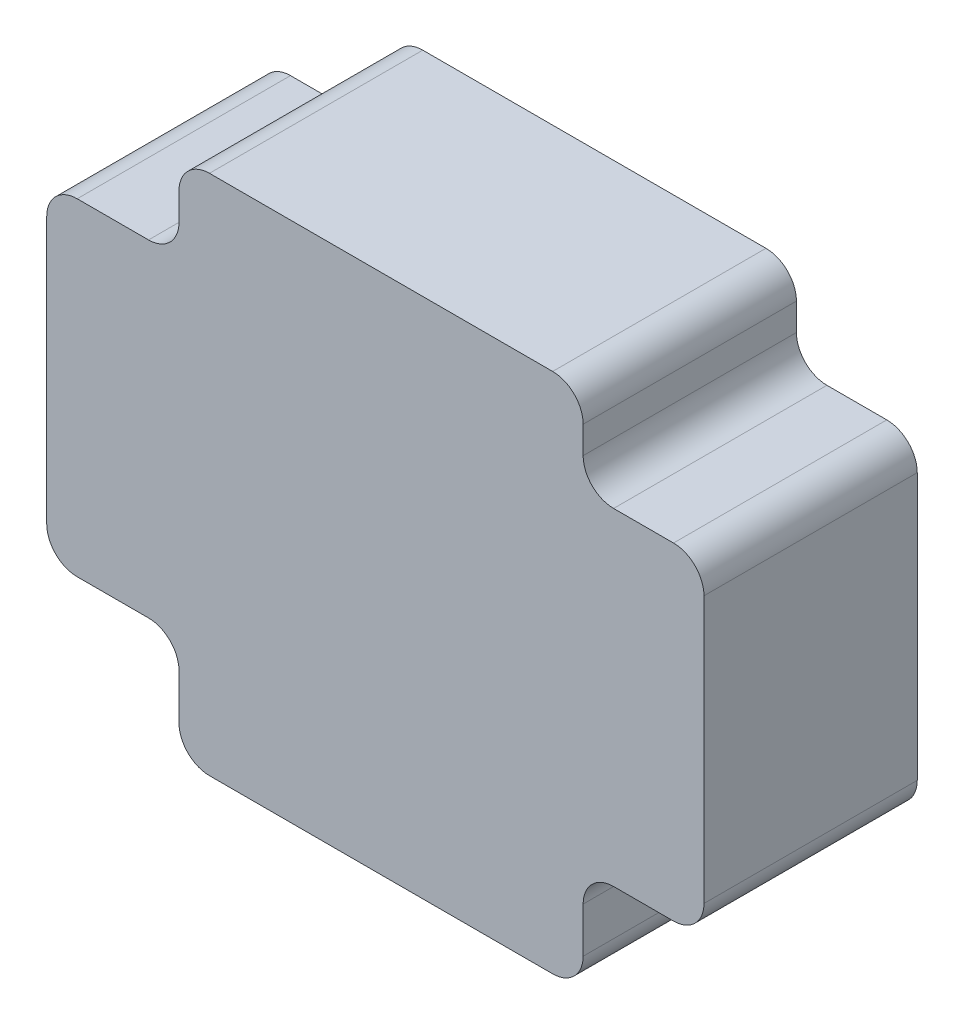
SolidWorks part; units mm, degrees
ref_plane "Front Plane" through (0, 0, 0) normal (0, 0, 1) x (1, 0, 0)
ref_plane "Top Plane" through (0, 0, 0) normal (0, 1, 0) x (1, 0, 0)
ref_plane "Right Plane" through (0, 0, 0) normal (1, 0, 0) x (0, 0, -1)
sketch "Sketch1" plane through (0, 0, 0) normal (0, 0, 1) x (1, 0, 0)
  line L0 (76.3168, 53.7233) -> (95.9729, 53.7233)
  line L1 (-99.7242, -53.7233) -> (-76.3168, -53.7233)
  line L2 (-109.7242, -43.7233) -> (-109.7242, 43.7233)
  line L3 (-99.7242, 53.7233) -> (-76.3168, 53.7233)
  line L4 (105.9729, -43.7233) -> (105.9729, 43.7233)
  line L7 (-56.3168, -88.5564) -> (56.3168, -88.5564)
  line L8 (-66.3168, -78.5564) -> (-66.3168, -63.7233)
  line L9 (-56.3168, 82.6615) -> (56.3168, 82.6615)
  line L10 (66.3168, -78.5564) -> (66.3168, -63.7233)
  line L15 (76.3168, -53.7233) -> (95.9729, -53.7233)
  line L16 (-66.3168, 63.7233) -> (-66.3168, 72.6615)
  line L17 (66.3168, 63.7233) -> (66.3168, 72.6615)
  arc A0 (-76.3168, -53.7233) -> (-66.3168, -63.7233) centre (-76.3168, -63.7233) cw
  arc A1 (66.3168, -63.7233) -> (76.3168, -53.7233) centre (76.3168, -63.7233) cw
  arc A2 (76.3168, 53.7233) -> (66.3168, 63.7233) centre (76.3168, 63.7233) cw
  arc A3 (-76.3168, 53.7233) -> (-66.3168, 63.7233) centre (-76.3168, 63.7233) ccw
  arc A4 (-109.7242, 43.7233) -> (-99.7242, 53.7233) centre (-99.7242, 43.7233) cw
  arc A5 (-99.7242, -53.7233) -> (-109.7242, -43.7233) centre (-99.7242, -43.7233) cw
  arc A6 (95.9729, -53.7233) -> (105.9729, -43.7233) centre (95.9729, -43.7233) ccw
  arc A7 (95.9729, 53.7233) -> (105.9729, 43.7233) centre (95.9729, 43.7233) cw
  arc A8 (56.3168, 82.6615) -> (66.3168, 72.6615) centre (56.3168, 72.6615) cw
  arc A9 (-66.3168, 72.6615) -> (-56.3168, 82.6615) centre (-56.3168, 72.6615) cw
  arc A10 (56.3168, -88.5564) -> (66.3168, -78.5564) centre (56.3168, -78.5564) ccw
  arc A11 (-56.3168, -88.5564) -> (-66.3168, -78.5564) centre (-56.3168, -78.5564) cw
  point P0 (0, 0)
  point P5 (0, 0)
  point P21 (66.3168, 53.7233)
  point P24 (-66.3168, 53.7233)
  point P25 (0, 0)
  dimension "D1" = 10
  dimension "D2" = 10
  dimension "D3" = 10
extrude "Boss-Extrude1" add sketch "Sketch1" along normal blind 70 contours L9 A8 L17 A2 L0 A7 L4 A6 L15 A1 L10 A10 L7 A11 L8 A0 L1 A5 L2 A4 L3 A3 L16 A9
shell "Shell1" thickness 8
sketch "Sketch3" plane through (0, 0, 0) normal (0, 0, 1) x (1, 0, 0)
  line L0 (-34.1038, 74.6615) -> (-34.1038, -80.5564)
  line L1 (2.7284, 74.6615) -> (2.7284, -80.5564)
  line L2 (36.9634, 74.6615) -> (36.9634, -80.5564)
  line L3 (97.9729, 2.3649) -> (-101.7242, 2.3649)
  line L4 (-56.3168, 74.6615) -> (56.3168, 74.6615) construction
  line L5 (-56.3168, -80.5564) -> (56.3168, -80.5564) construction
  line L6 (-56.3168, 74.6615) -> (56.3168, 74.6615) construction
  line L7 (97.9729, -43.7233) -> (97.9729, 43.7233) construction
  line L8 (-101.7242, -43.7233) -> (-101.7242, 43.7233) construction
  point P9 (-33.6315, 74.6615)
  point P12 (-34.1038, -80.5564)
  point P15 (4.6172, 74.6615)
  point P18 (2.7284, -80.5564)
  point P19 (38.8522, 74.6615)
  point P20 (36.9634, -80.5564)
  point P21 (97.9729, 4.7259)
  point P24 (-101.7242, 2.3649)
rib "Rib15" sketch "Sketch3" sketch "Sketch3" thickness 5 extrusion direction normal to sketch draft on no parameters "D1"=5
